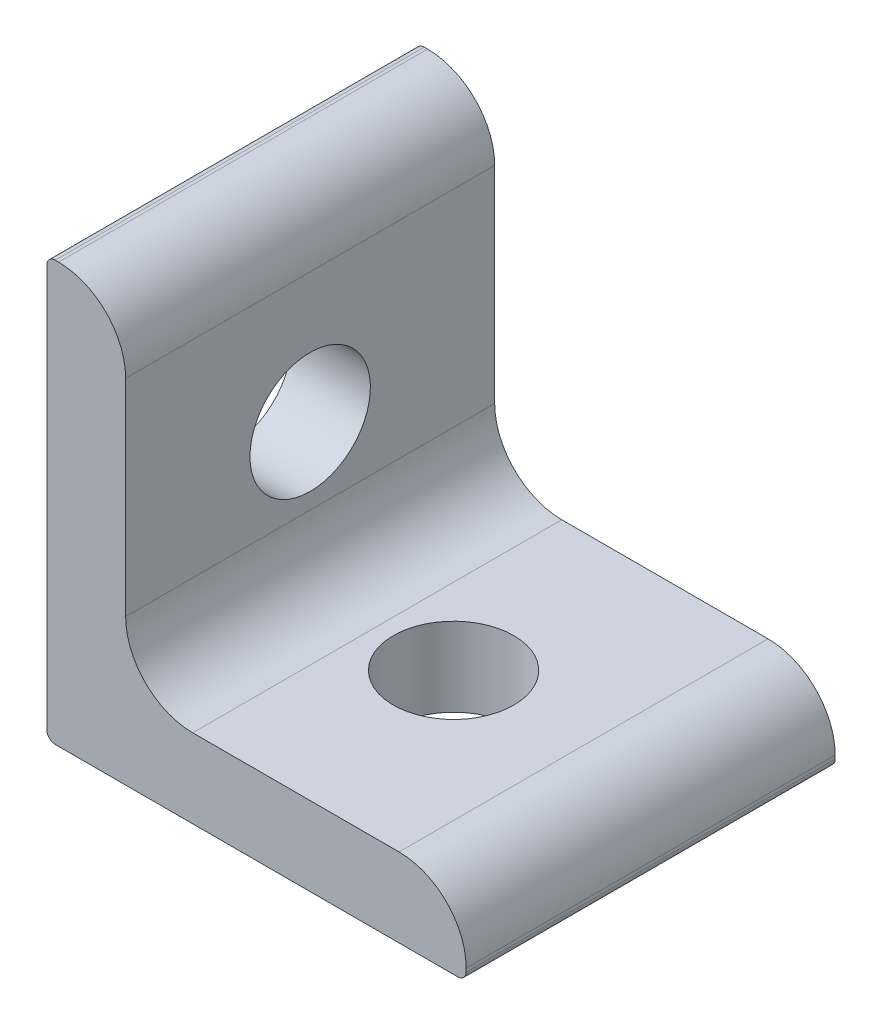
SolidWorks part; units mm, degrees
ref_plane "Front Plane" through (0, 0, 0) normal (0, 0, 1) x (1, 0, 0)
ref_plane "Top Plane" through (0, 0, 0) normal (0, 1, 0) x (1, 0, 0)
ref_plane "Right Plane" through (0, 0, 0) normal (1, 0, 0) x (0, 0, -1)
sketch "Sketch1" plane through (0, 0, 0) normal (0, 0, 1) x (1, 0, 0)
  line L0 (0, 0) -> (25, 0)
  line L1 (25, 0) -> (25, 4.7)
  line L2 (25, 4.7) -> (4.7, 4.7)
  line L3 (4.7, 4.7) -> (4.7, 25)
  line L4 (4.7, 25) -> (0, 25)
  line L5 (0, 25) -> (0, 0)
  dimension "D1" = 25
  dimension "D2" = 4.7
extrude "Boss-Extrude1" add sketch "Sketch1" along normal blind 22
sketch "Sketch2" plane through (0, 0, 0) normal (0, -1, 0) x (1, 0, 0)
  line L0 (13.25, 11) -> (0, 11) construction
  line L2 (0, 22) -> (0, 0) construction
  circle A0 centre (13.25, 11) radius 3.59
  dimension "D1" = 7.18
  dimension "D2" = 13.25
extrude "Cut-Extrude1" cut sketch "Sketch2" against normal through all
sketch "Sketch3" plane through (0, 0, 0) normal (-1, 0, 0) x (0, 0, 1)
  line L0 (11, 13.25) -> (11, 0) construction
  line L1 (22, 0) -> (0, 0) construction
  circle A0 centre (11, 13.25) radius 3.59
  dimension "D1" = 7.18
  dimension "D2" = 13.25
extrude "Cut-Extrude2" cut sketch "Sketch3" against normal through all
fillet "Fillet1" radius 4 3 edges at (25, 4.7, 11) (4.7, 4.7, 11) (4.7, 25, 11)
fillet "Fillet2" radius 0.5 3 edges at (25, 0, 11) (0, 0, 11) (0, 25, 11)
ref_plane "Plane1" through (0, 0, 11) normal (0, 0, 1) x (1, 0, 0)
